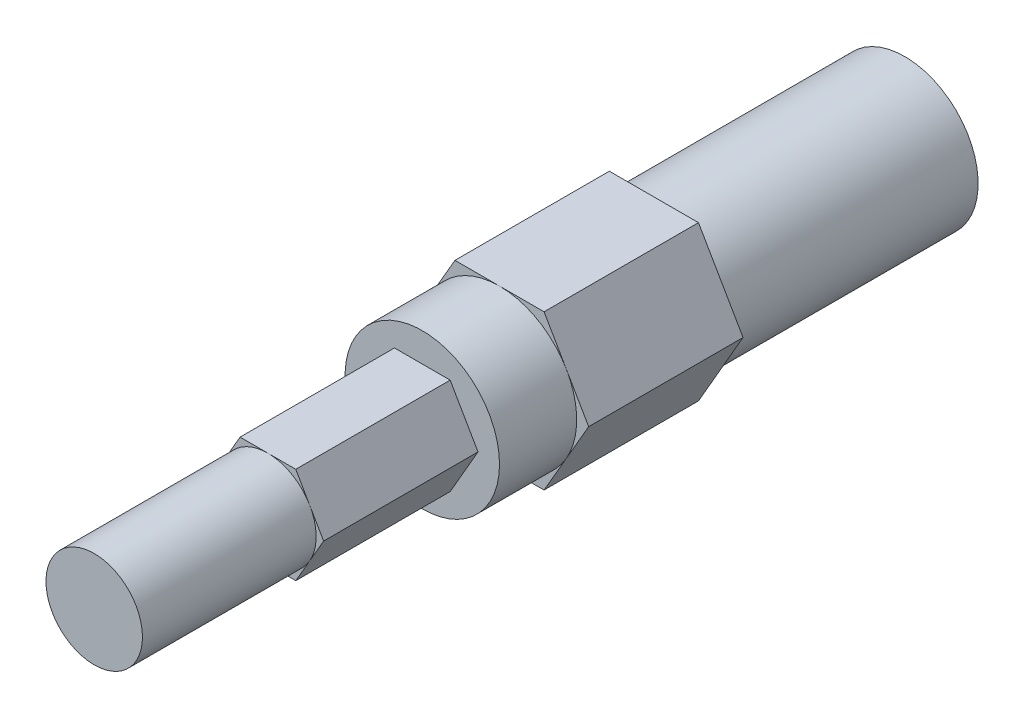
SolidWorks part; units mm, degrees
material "ABS"
ref_plane "Front Plane" through (0, 0, 0) normal (0, 0, 1) x (1, 0, 0)
ref_plane "Top Plane" through (0, 0, 0) normal (0, 1, 0) x (1, 0, 0)
ref_plane "Right Plane" through (0, 0, 0) normal (1, 0, 0) x (0, 0, -1)
sketch "Sketch1" plane through (0, 0, 0) normal (0, 0, 1) x (1, 0, 0)
  circle A0 centre (0, 0) radius 2.413
  dimension "D1" = 4.826
extrude "Boss-Extrude1" add sketch "Sketch1" along normal blind 13.335
sketch "Sketch2" plane through (0, 0, 13.335) normal (0, 0, 1) x (1, 0, 0)
  line L1 (2.9329, 0) -> (1.4665, 2.54)
  line L2 (1.4665, 2.54) -> (-1.4665, 2.54)
  line L3 (-1.4665, 2.54) -> (-2.9329, 0)
  line L4 (-2.9329, 0) -> (-1.4665, -2.54)
  line L5 (-1.4665, -2.54) -> (1.4665, -2.54)
  line L6 (1.4665, -2.54) -> (2.9329, 0)
  circle A0 centre (0, 0) radius 2.54 construction
  dimension "D1" = 5.08
extrude "Boss-Extrude2" add sketch "Sketch2" along normal blind 5.08
sketch "Sketch3" plane through (0, 0, 0) normal (0, 0, -1) x (-1, 0, 0)
  circle A1 centre (0, 0) radius 2.413
  circle A2 centre (0, 0) radius 2.413
  dimension "D1" = 0
extrude "Cut-Extrude1" cut sketch "Sketch3" against normal blind 1.905
sketch "Sketch4" plane through (0, 0, 18.415) normal (0, 0, 1) x (1, 0, 0)
  circle A0 centre (0, 0) radius 2.54
extrude "Boss-Extrude3" add sketch "Sketch4" along normal blind 2.54
sketch "Sketch5" plane through (0, 0, 20.955) normal (0, 0, 1) x (1, 0, 0)
  line L1 (1.8331, 0) -> (0.9165, 1.5875)
  line L2 (0.9165, 1.5875) -> (-0.9165, 1.5875)
  line L3 (-0.9165, 1.5875) -> (-1.8331, 0)
  line L4 (-1.8331, 0) -> (-0.9165, -1.5875)
  line L5 (-0.9165, -1.5875) -> (0.9165, -1.5875)
  line L6 (0.9165, -1.5875) -> (1.8331, 0)
  circle A0 centre (0, 0) radius 1.5875 construction
  dimension "D1" = 3.175
extrude "Boss-Extrude4" add sketch "Sketch5" along normal blind 5.08 contours L1 L2 L3 L4 L5 L6
sketch "Sketch6" plane through (0, 0, 26.035) normal (0, 0, 1) x (1, 0, 0)
  circle A0 centre (0, 0) radius 1.5875
extrude "Boss-Extrude5" add sketch "Sketch6" along normal blind 5.715
sketch "Sketch7" plane through (0, 0, 1.905) normal (0, 0, -1) x (-1, 0, 0)
  circle A1 centre (0, 0) radius 2.413
  circle A2 centre (0, 0) radius 2.413
  dimension "D1" = 0
extrude "Cut-Extrude2" cut sketch "Sketch7" against normal blind 3.175
